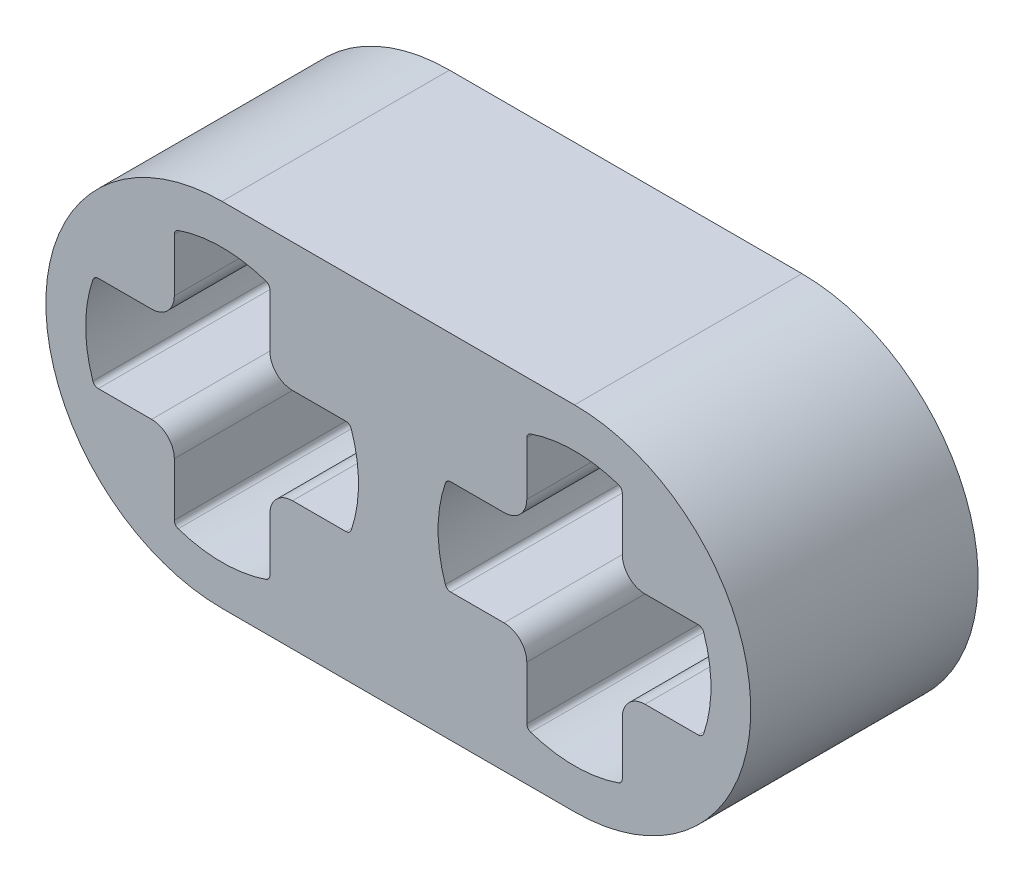
SolidWorks part; units mm, degrees
ref_plane "Front Plane" through (0, 0, 0) normal (0, 0, 1) x (1, 0, 0)
ref_plane "Top Plane" through (0, 0, 0) normal (0, 1, 0) x (1, 0, 0)
ref_plane "Right Plane" through (0, 0, 0) normal (1, 0, 0) x (0, 0, -1)
sketch "Sketch2" plane through (0, 0, 0) normal (0, 0, 1) x (1, 0, 0)
  line L0 (-3.1, 3.1) -> (3.1, 3.1)
  line L1 (-3.1, 0) -> (3.1, 0) construction
  line L2 (-3.1, -3.1) -> (3.1, -3.1)
  arc A0 (-3.1, 3.1) -> (-3.1, -3.1) centre (-3.1, 0) ccw
  arc A1 (3.1, -3.1) -> (3.1, 3.1) centre (3.1, 0) ccw
  dimension "D2" = 6.2
  dimension "D3" = 6.2
  dimension "D1" = 6.2
  dimension "D4" = 6.2
  dimension "D5" = 6.2
extrude "Boss-Extrude1" add sketch "Sketch2" against normal blind 4
sketch "Sketch4" plane through (0, 0, 0) normal (0, 0, 1) x (1, 0, 0)
  line L0 (-3.94, -0.84) -> (-3.94, -2.2482)
  line L2 (-3.94, 2.2482) -> (-3.94, 0.84)
  line L4 (-2.26, 2.2482) -> (-2.26, 0.84)
  line L5 (-3.94, 2.2482) -> (-2.26, -2.2482) construction
  line L6 (-3.94, -2.2482) -> (-2.26, 2.2482) construction
  line L7 (-0.8518, 0.84) -> (-2.26, 0.84)
  line L9 (-0.8518, -0.84) -> (-2.26, -0.84)
  line L11 (-0.8518, 0.84) -> (-5.3482, -0.84) construction
  line L12 (-0.8518, -0.84) -> (-5.3482, 0.84) construction
  line L17 (-3.94, 0.84) -> (-5.3482, 0.84)
  line L18 (-3.94, -0.84) -> (-5.3482, -0.84)
  line L19 (-2.26, -0.84) -> (-2.26, -2.2482)
  arc A0 (-2.26, 2.2482) -> (-3.94, 2.2482) centre (-3.1, 0) ccw
  arc A2 (-5.3482, 0.84) -> (-5.3482, -0.84) centre (-3.1, 0) ccw
  arc A3 (-3.94, -2.2482) -> (-2.26, -2.2482) centre (-3.1, 0) ccw
  arc A4 (-0.8518, -0.84) -> (-0.8518, 0.84) centre (-3.1, 0) ccw
  dimension "D1" = 4.8
  dimension "D3" = 1.68
  dimension "D4" = 1.68
extrude "Cut-Extrude1" cut sketch "Sketch4" against normal through all contours A0 L2 L17 A2 L18 L0 A3 L19 L9 A4 L7 L4
fillet "Fillet1" radius 0.4 1 edges at (-3.94, -0.84, -2)
fillet "Fillet2" radius 0.4 1 edges at (-3.94, 0.84, -2)
fillet "Fillet3" radius 0.4 1 edges at (-2.26, 0.84, -2)
fillet "Fillet4" radius 0.4 1 edges at (-2.26, -0.84, -2)
fillet "Fillet5" radius 0.1 1 edges at (-3.94, -2.2482, -2)
fillet "Fillet6" radius 0.1 1 edges at (-2.26, -2.2482, -2)
fillet "Fillet7" radius 0.1 1 edges at (-0.8518, 0.84, -2)
fillet "Fillet8" radius 0.1 1 edges at (-0.8518, -0.84, -2)
fillet "Fillet9" radius 0.1 1 edges at (-2.26, 2.2482, -2)
fillet "Fillet10" radius 0.1 1 edges at (-3.94, 2.2482, -2)
fillet "Fillet11" radius 0.1 1 edges at (-5.3482, 0.84, -2)
fillet "Fillet12" radius 0.1 1 edges at (-5.3482, -0.84, -2)
mirror "Mirror1" about plane through (0, 0, 0) normal (1, 0, 0) of "Cut-Extrude1", "Fillet1", "Fillet2", "Fillet3", "Fillet4", "Fillet5", "Fillet6", "Fillet7", "Fillet8", "Fillet9", "Fillet10", "Fillet11", "Fillet12"
